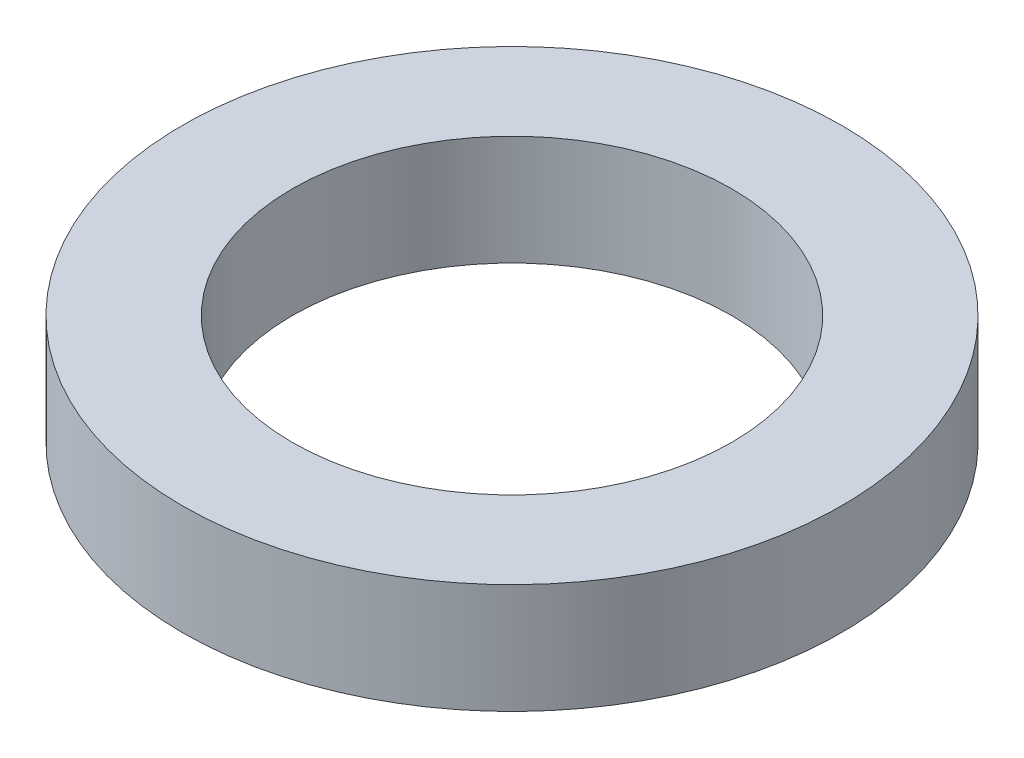
SolidWorks part; units mm, degrees
material "Brass"
ref_plane "Front Plane" through (0, 0, 0) normal (0, 0, 1) x (1, 0, 0)
ref_plane "Top Plane" through (0, 0, 0) normal (0, 1, 0) x (1, 0, 0)
ref_plane "Right Plane" through (0, 0, 0) normal (1, 0, 0) x (0, 0, -1)
sketch "Sketch1" plane through (0, 0, 0) normal (0, 1, 0) x (1, 0, 0)
  circle A0 centre (0, 0) radius 6.35
  circle A1 centre (0, 0) radius 9.525
  dimension "D1" = 19.05
  dimension "D2" = 12.7
extrude "Boss-Extrude1" add sketch "Sketch1" along normal blind 3.175
